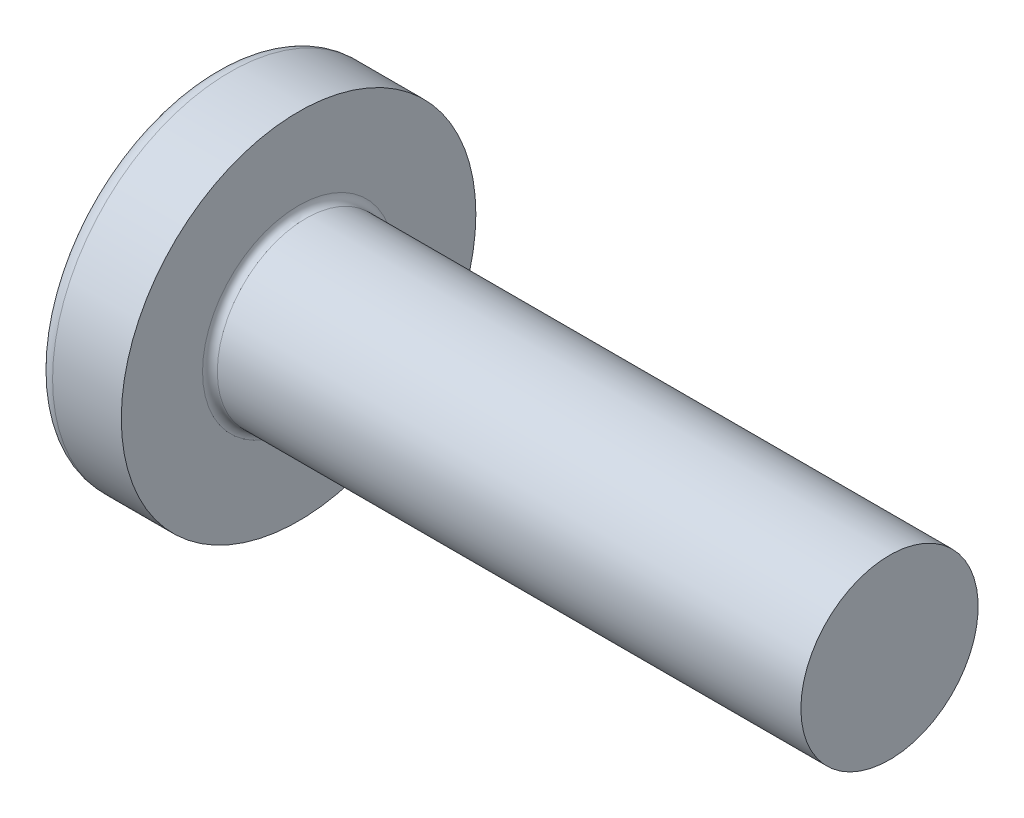
SolidWorks part; units mm, degrees
ref_plane "Plane1" through (0, 0, 0) normal (0, 0, 1) x (1, 0, 0)
ref_plane "Plane2" through (0, 0, 0) normal (0, 1, 0) x (1, 0, 0)
ref_plane "Plane3" through (0, 0, 0) normal (1, 0, 0) x (0, 0, -1)
sketch "BodySke" plane through (0, 0, 0) normal (0, 0, 1) x (1, 0, 0)
  line L0 (4.6, 3) -> (4.6, 6)
  line L1 (5.1, 6.35) -> (5.1, -3.175) construction
  line L2 (-25.4, 0) -> (127, 0) construction
  line L3 (24.6, 0) -> (0, 0)
  line L4 (4.6, 3) -> (24.6, 3)
  line L5 (24.6, 3) -> (24.6, 0)
  line L6 (2.2747, 6) -> (4.6, 6)
  line L8 (-5.4, 6.35) -> (-5.4, -3.175) construction
  arc A0 (1.8337, 5.7717) -> (0, 0) centre (10, 0) ccw
  arc A2 (1.8337, 5.7717) -> (2.2747, 6) centre (2.2747, 5.46) cw
  dimension "Head_crown_rad" = 10
  dimension "Head_fillet_rad" = 0.54
  dimension "Length" = 20
  dimension "Head_ht" = 4.6
  dimension "Head_dia" = 12
  dimension "Advance" = 1
  dimension "Thread_nom" = 30
  dimension "Diameter" = 6
revolve "Base-Revolve" add sketch "BodySke"
cosmetic thread "ThreadCosmetic" [suppressed]
fillet "Fillet1" radius 0.25 1 edges at (4.6, 0, 3)
sketch "Sketch3" plane through (0, 0, 0) normal (1, 0, 0) x (0, 0, -1)
  line L0 (0.71, -3.35) -> (-0.71, -3.35)
  line L1 (0.71, -3.35) -> (0.71, 3.35)
  line L2 (-0.71, 3.35) -> (0.71, 3.35)
  line L3 (-0.71, 3.35) -> (-0.71, -3.35)
  dimension "Cross_dia" = 6.7
  dimension "D1" = 3.35
  dimension "Cross_width" = 1.42
  dimension "D2" = 0.71
ref_plane "Plane4" through (3.46, 0, 0) normal (1, 0, 0) x (0, 0, -1)
sketch "Sketch4" plane through (3.46, 0, 0) normal (1, 0, 0) x (0, 0, -1)
  line L0 (0.71, -1.6249) -> (-0.71, -1.6249)
  line L1 (0.71, -1.6249) -> (0.71, 1.6249)
  line L2 (-0.71, 1.6249) -> (0.71, 1.6249)
  line L3 (-0.71, 1.6249) -> (-0.71, -1.6249)
  dimension "D1" = 1.42
  dimension "D2" = 3.2498
  dimension "D3" = 0.71
  dimension "D4" = 1.6249
loft "Recess" cut profiles "Sketch3", "Sketch4"
pattern_circular "RecPat" count 2 every 90 about axis through (0, 0, 0) along (1, 0, 0) of "Recess"
sketch "RecCorSke" plane through (0, 0, 0) normal (0, 0, 1) x (1, 0, 0)
  line L0 (-3.175, 0) -> (15.875, 0) construction
  line L1 (-25.4, 0) -> (127, 0) construction
  line L2 (0, 0) -> (0, 1.5224)
  line L3 (0, 1.5224) -> (3.46, 1.2805)
  line L4 (3.46, 1.2805) -> (3.8761, 0)
  line L5 (3.8761, 0) -> (0, 0)
  dimension "Diameter" = 2.561
  dimension "Depth" = 3.46
  dimension "Draft_angle" = 4
  dimension "Bottom_angle" = 18
revolve "RecessCore" cut sketch "RecCorSke" angle 360 about L0
sketch "ThdSchSke" plane through (0, 0, 0) normal (0, 0, 1) x (1, 0, 0)
  line L0 (6.6, -2.4455) -> (6.2117, -3)
  line L1 (6.6, -2.4455) -> (6.9883, -3)
  line L2 (6.9883, -3) -> (6.9883, -3.75)
  line L3 (-3.175, 0) -> (5.1513, 0) construction
  line L5 (6.9883, -3.75) -> (6.2117, -3.75)
  line L6 (6.2117, -3.75) -> (6.2117, -3)
  dimension "Diameter" = 6
  dimension "SideAngle" = 55
  dimension "VeeAngle" = 70
  dimension "Thread_minor" = 4.891
  dimension "Overcut" = 7.5
  dimension "Start" = 6.6
revolve "ThreadSchematic" [suppressed] cut sketch "ThdSchSke" angle 360 about L3
pattern_linear "ThdSchPat" [suppressed]
equation "\"D1@Sketch3\" = \"Cross_dia@Sketch3\" / 2"
equation "\"D2@Sketch3\" = \"Cross_width@Sketch3\" / 2"
equation "\"Depth@RecCorSke\" = \"Cross_depth@Plane4\""
equation "\"D1@Sketch4\" = \"Cross_width@Sketch3\""
equation "\"D2@Sketch4\" = \"Cross_dia@Sketch3\" - 2.0 * \"Cross_depth@Plane4\" * tan(26.5  * 0.017453292)"
equation "\"D3@Sketch4\" = \"D1@Sketch4\" / 2"
equation "\"D4@Sketch4\" = \"D2@Sketch4\" / 2"
equation "\"Thread_length@ThreadCosmetic\" = ((sgn( (\"Length@BodySke\" - \"Advance@BodySke\" * 2.0 ) - \"Thread_nom@BodySke\" )-1)*( (\"Length@BodySke\" - \"Advance@BodySke\" * 2.0 ) - \"Thread_nom@BodySke\" ))/-2+ \"Thread_nom@BodySke\""
equation "\"Thread_minor@ThdSchSke\" = \"Thread_minor@ThreadCosmetic\""
equation "\"Diameter@ThdSchSke\" = \"Diameter@BodySke\""
equation "\"Overcut@ThdSchSke\" = \"Diameter@BodySke\" * 1.25"
equation "\"Start@ThdSchSke\" = \"Head_ht@BodySke\" + \"Length@BodySke\" - \"Thread_length@ThreadCosmetic\"  '---Non-countersunk---"
equation "\"Num_threads@ThdSchPat\" = int( \"Thread_length@ThreadCosmetic\" / \"Advance@BodySke\" + 0.999 )  + 1"
equation "\"Advance@ThdSchPat\" = \"Thread_length@ThreadCosmetic\" /  (\"Num_threads@ThdSchPat\" - 1) 'relax it"
